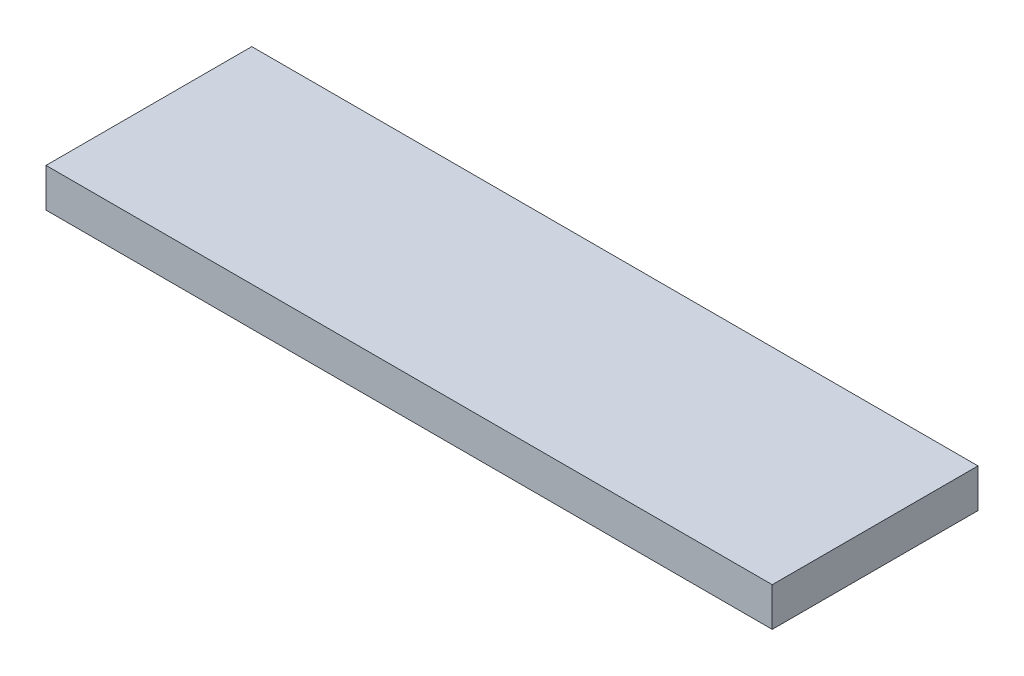
SolidWorks part; units mm, degrees
ref_plane "Front Plane" through (0, 0, 0) normal (0, 0, 1) x (1, 0, 0)
ref_plane "Top Plane" through (0, 0, 0) normal (0, 1, 0) x (1, 0, 0)
ref_plane "Right Plane" through (0, 0, 0) normal (1, 0, 0) x (0, 0, -1)
sketch "Sketch1" plane through (0, 0, 0) normal (0, 1, 0) x (1, 0, 0)
  line L1 (0, 0) -> (30, 0)
  line L2 (0, 0) -> (0, 8.5)
  line L3 (0, 8.5) -> (30, 8.5)
  line L4 (30, 0) -> (30, 8.5)
  dimension "D1" = 8.5
  dimension "D2" = 30
extrude "Boss-Extrude1" add sketch "Sketch1" along normal blind 1.6
equation "\"leftedgewidth\" = 8.5mm"
equation "\"rightedgewidth\" = 10.75mm"
equation "\"innerclipwidth\" = 11.5mm"
equation "\"innerframewidth\" = 99.18mm"
equation "\"framelength\" = 103.2mm"
equation "\"frameextralength\" = 39mm"
equation "\"clipwidth\" = 3mm"
equation "\"cliplength\" = 6mm"
equation "\"clipheight\" = 8mm"
equation "\"basethickness\" = 5mm"
equation "\"framethickness\" = 1.6mm"
equation "\"batterylength\" = 145mm"
equation "\"batterywidth\" = 51mm"
equation "\"D1@Sketch1\"=\"leftedgewidth\""
